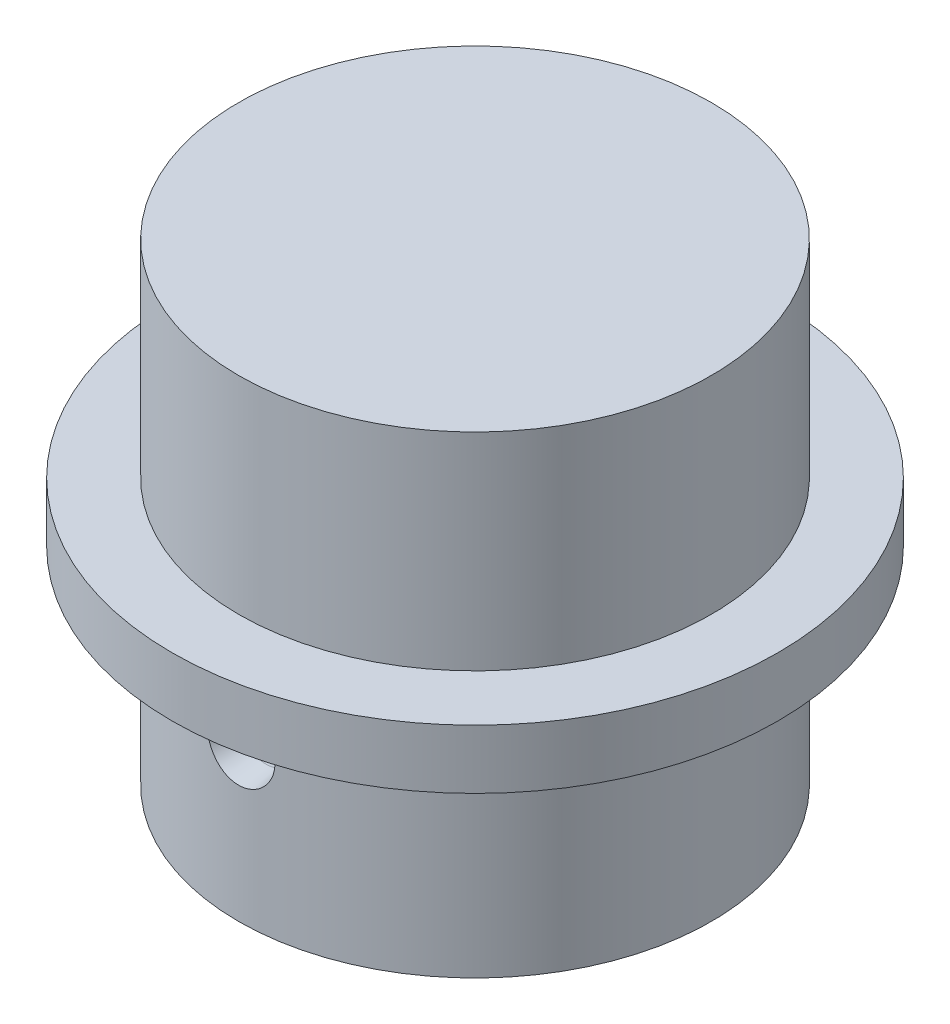
SolidWorks part; units mm, degrees
ref_plane "Front Plane" through (0, 0, 0) normal (0, 0, 1) x (1, 0, 0)
ref_plane "Top Plane" through (0, 0, 0) normal (0, 1, 0) x (1, 0, 0)
ref_plane "Right Plane" through (0, 0, 0) normal (1, 0, 0) x (0, 0, -1)
sketch "Sketch1" plane through (0, 0, 0) normal (0, 1, 0) x (1, 0, 0)
  circle A0 centre (0, 0) radius 16
extrude "Extrude1" add sketch "Sketch1" along normal blind 32
sketch "Sketch2" plane through (0, 0, 0) normal (0, -1, 0) x (1, 0, 0)
  circle A0 centre (0, 0) radius 3.175
extrude "Extrude2" cut sketch "Sketch2" against normal blind 18.5
sketch "Sketch3" plane through (0, 0, 0) normal (0, 0, 1) x (1, 0, 0)
  line L1 (-13.7079, 0) -> (-12.6622, 2.0599)
  line L2 (-16, 0) -> (16, 0) construction
  line L3 (-11.8851, 0.277) -> (-11.8851, 3.0961) construction
  line L4 (-10.0623, 0) -> (-11.108, 2.0599)
  line L5 (-12.6622, 2.0599) -> (-11.108, 2.0599)
  line L6 (-13.7079, 0) -> (-10.0623, 0)
sketch "Sketch4" plane through (0, 0, 0) normal (0, 1, 0) x (1, 0, 0)
  circle A0 centre (0, 0) radius 11.8914
sweep "Cut-Sweep1" cut profiles "Sketch3" path "Sketch4"
ref_plane "Plane1" through (0, 14, 0) normal (0, -1, 0) x (1, 0, 0)
sketch "Sketch5" plane through (0, 14, 0) normal (0, -1, 0) x (1, 0, 0)
  circle A0 centre (0, 0) radius 20.5
extrude "Extrude3" add sketch "Sketch5" against normal blind 4
sketch "Sketch6" plane through (0, 0, 0) normal (0, 0, 1) x (1, 0, 0)
  circle A0 centre (0, 10.3125) radius 2
extrude "Cut-Extrude1" cut sketch "Sketch6" against normal blind 20 from offset 20
sketch "Sketch7" plane through (0, 0, 0) normal (0, 0, 1) x (1, 0, 0)
  circle A0 centre (0, 10.3125) radius 2.8526
extrude "Cut-Extrude3" cut sketch "Sketch7" against normal blind 5 draft 10 from offset 19
